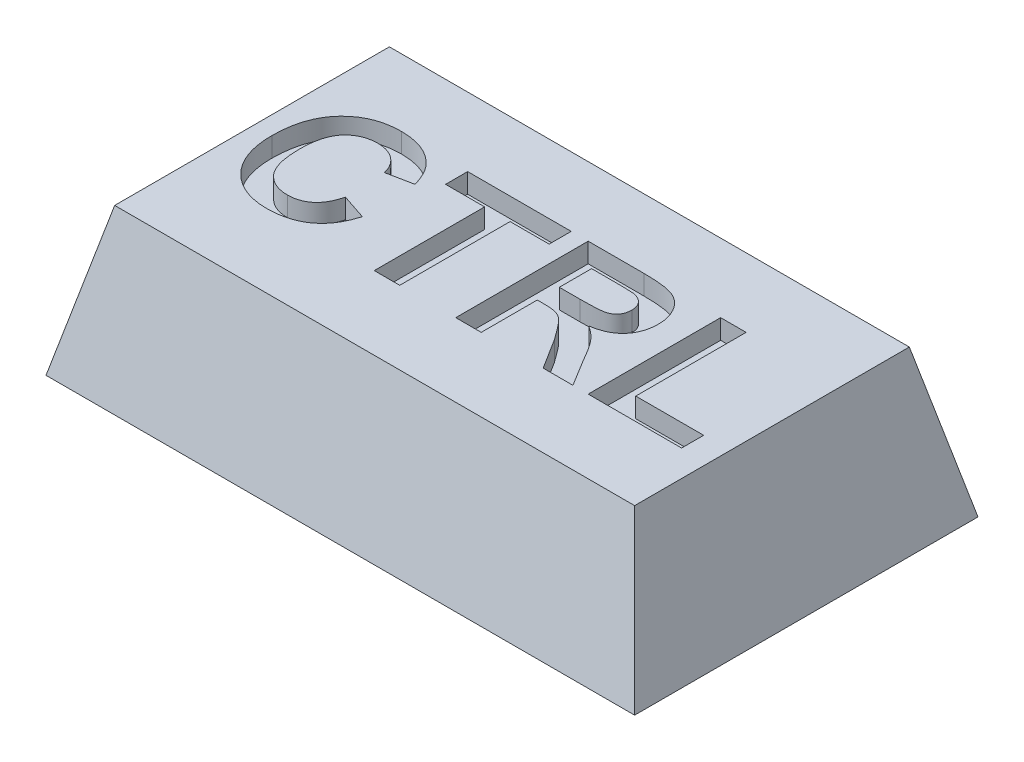
SolidWorks part; units mm, degrees
ref_plane "Front Plane" through (0, 0, 0) normal (0, 0, 1) x (1, 0, 0)
ref_plane "Top Plane" through (0, 0, 0) normal (0, 1, 0) x (1, 0, 0)
ref_plane "Right Plane" through (0, 0, 0) normal (1, 0, 0) x (0, 0, -1)
sketch "Sketch1" plane through (0, 0, 0) normal (0, 1, 0) x (1, 0, 0)
  line L1 (0, 0) -> (12, 0)
  line L2 (0, 0) -> (0, 7)
  line L3 (0, 7) -> (12, 7)
  line L4 (12, 0) -> (12, 7)
  dimension "D1" = 7
  dimension "D2" = 12
extrude "Boss-Extrude1" add sketch "Sketch1" along normal blind 3
sketch "Sketch2" plane through (0, 0, 0) normal (0, 0, 1) x (1, 0, 0)
  line L0 (0, 0) -> (0.7, 3)
  line L1 (0, 3) -> (12, 3) construction
  line L2 (0.7, 3) -> (0, 3)
  line L3 (0, 3) -> (0, 0)
  line L4 (12, 0) -> (11.3, 3)
  line L5 (11.3, 3) -> (12, 3)
  line L6 (12, 3) -> (12, 0)
  dimension "D1" = 0.7
  dimension "D2" = 0.7
extrude "Cut-Extrude1" cut sketch "Sketch2" against normal blind 7
sketch "Sketch3" plane through (0, 0, 0) normal (1, 0, 0) x (0, 0, -1)
  line L0 (0, 0) -> (0.7, 3)
  line L1 (7, 3) -> (0, 3) construction
  line L2 (0.7, 3) -> (0, 3)
  line L3 (0, 3) -> (0, 0)
  line L4 (7, 3) -> (6.3, 3)
  line L5 (6.3, 3) -> (7, 0)
  line L6 (7, 3) -> (7, 0)
  dimension "D1" = 0.7
  dimension "D2" = 0.7
extrude "Cut-Extrude2" cut sketch "Sketch3" along normal through all both and the other way through all
sketch "Sketch4" plane through (0, 0, 0) normal (0, -1, 0) x (1, 0, 0)
  line L0 (6, 0) -> (6, -7) construction
  line L1 (0, 0) -> (12, 0) construction
  line L2 (12, -7) -> (0, -7) construction
  line L3 (0, -3.5) -> (12, -3.5) construction
  line L4 (0, -7) -> (0, 0) construction
  line L5 (12, 0) -> (12, -7) construction
  circle A0 centre (6, -3.5) radius 1.8
  dimension "D1" = 3.6
extrude "Cut-Extrude3" cut sketch "Sketch4" against normal blind 0.8
sketch "Sketch5" plane through (0, 3, 0) normal (0, 1, 0) x (1, 0, 0)
  text T0 "CTRL" font "Arial" height 2.7
extrude "Cut-Extrude4" cut sketch "Sketch5" against normal blind 0.4
